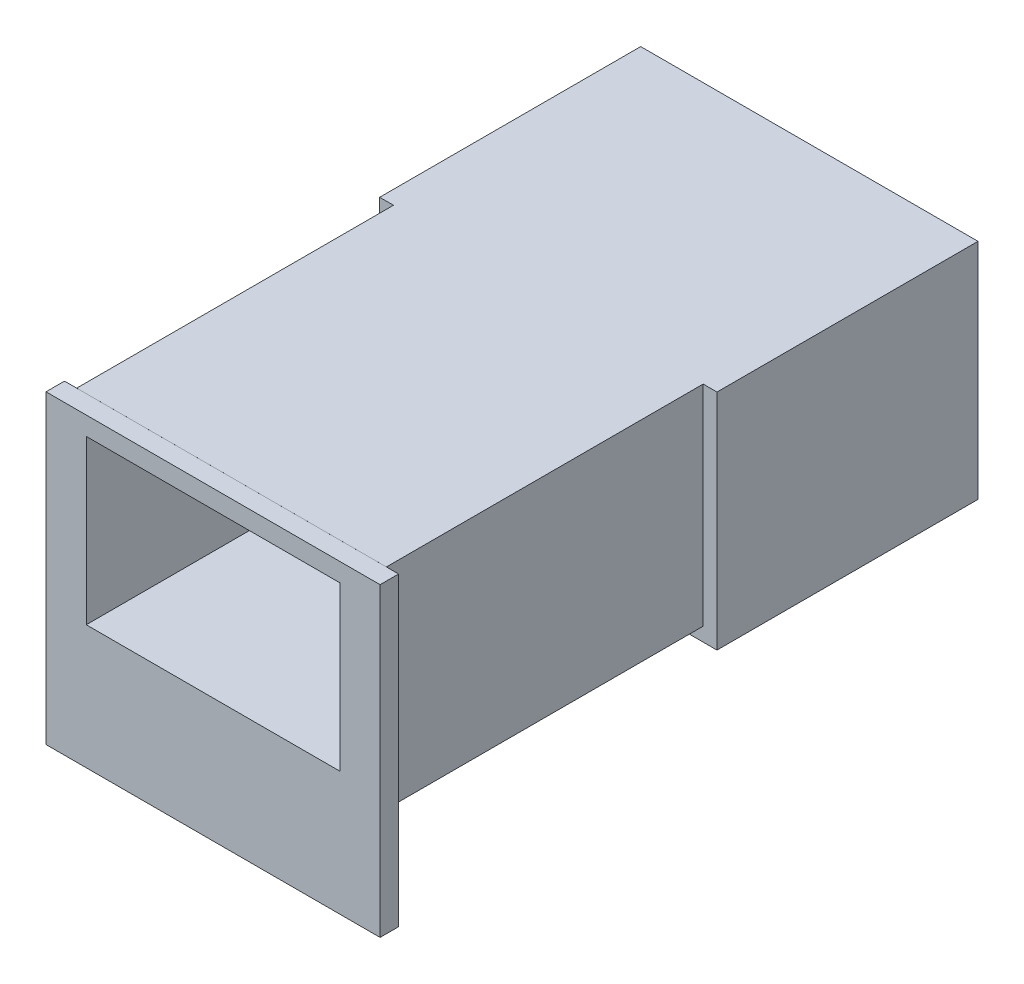
SolidWorks part; units mm, degrees
ref_plane "Alzado" through (0, 0, 0) normal (0, 0, 1) x (1, 0, 0)
ref_plane "Planta" through (0, 0, 0) normal (0, 1, 0) x (1, 0, 0)
ref_plane "Vista lateral" through (0, 0, 0) normal (1, 0, 0) x (0, 0, -1)
sketch "Croquis1" plane through (0, 0, 0) normal (0, 0, 1) x (1, 0, 0)
  line L1 (-37.1318, 17.9473) -> (16.1082, 17.9473)
  line L2 (-37.1318, 17.9473) -> (-37.1318, -17.3327)
  line L3 (-37.1318, -17.3327) -> (16.1082, -17.3327)
  line L4 (16.1082, 17.9473) -> (16.1082, -17.3327)
  line L5 (-33.9518, 15.0273) -> (12.9282, 15.0273)
  line L6 (-33.9518, 15.0273) -> (-33.9518, -14.1527)
  line L7 (-33.9518, -14.1527) -> (12.9282, -14.1527)
  line L8 (12.9282, 15.0273) -> (12.9282, -14.1527)
  dimension "D1" = 53.24
  dimension "D2" = 35.28
  dimension "D3" = 3.18
  dimension "D4" = 3.18
  dimension "D5" = 3.18
  dimension "D6" = 2.92
extrude "Saliente-Extruir2" add sketch "Croquis1" along normal blind 41.2
sketch "Croquis3" plane through (0, 0, 41.2) normal (0, 0, 1) x (1, 0, 0)
  line L1 (-34.9518, -15.1527) -> (13.9282, -15.1527)
  line L2 (-34.9518, -15.1527) -> (-34.9518, 17.9473)
  line L3 (-34.9518, 17.9473) -> (13.9282, 17.9473)
  line L4 (13.9282, -15.1527) -> (13.9282, 17.9473)
  line L5 (12.9282, -14.1527) -> (12.9282, 15.0273) construction
  line L7 (9.4982, 15.0273) -> (-30.5218, 15.0273)
  line L8 (9.4982, 15.0273) -> (9.4982, -10.7227)
  line L9 (9.4982, -10.7227) -> (-30.5218, -10.7227)
  line L10 (-30.5218, 15.0273) -> (-30.5218, -10.7227)
  line L12 (-34.9518, 17.9473) -> (13.9282, 17.9473)
  line L13 (-34.9518, 17.9473) -> (-34.9518, -15.1527)
  line L14 (-34.9518, -15.1527) -> (13.9282, -15.1527)
  line L15 (13.9282, 17.9473) -> (13.9282, -15.1527)
  line L16 (-30.5218, 15.0273) -> (9.4982, 15.0273)
  line L17 (-30.5218, 15.0273) -> (-30.5218, -10.7227)
  line L18 (-30.5218, -10.7227) -> (9.4982, -10.7227)
  line L19 (9.4982, 15.0273) -> (9.4982, -10.7227)
  line L20 (13.9282, -15.1527) -> (-34.9518, -15.1527)
  line L21 (13.9282, -15.1527) -> (13.9282, 17.9473)
  line L22 (13.9282, 17.9473) -> (-34.9518, 17.9473)
  line L23 (-34.9518, -15.1527) -> (-34.9518, 17.9473)
  line L24 (9.4982, -10.7227) -> (-30.5218, -10.7227)
  line L25 (9.4982, -10.7227) -> (9.4982, 15.0273)
  line L26 (9.4982, 15.0273) -> (-30.5218, 15.0273)
  line L27 (-30.5218, -10.7227) -> (-30.5218, 15.0273)
  dimension "D1" = 1
  dimension "D2" = 25.75
  dimension "D3" = 4.43
  dimension "D4" = 40.02
  dimension "D5" = 4.43
extrude "Saliente-Extruir11" add sketch "Croquis3" along normal blind 50 contours L10 L9 L8 L7 | L2 L3 L4 L1
sketch "Croquis15" plane through (0, 0, 91.2) normal (0, 0, 1) x (1, 0, 0)
  line L1 (15.8532, -30.2747) -> (-36.8768, -30.2747)
  line L2 (15.8532, -30.2747) -> (15.8532, 17.9453)
  line L3 (15.8532, 17.9453) -> (-36.8768, 17.9453)
  line L4 (-36.8768, -30.2747) -> (-36.8768, 17.9453)
  line L5 (13.9282, -15.1527) -> (13.9282, 17.9473) construction
  line L6 (-34.9518, -15.1527) -> (-34.9518, 17.9473) construction
  line L7 (-34.9518, -15.1527) -> (13.9282, -15.1527) construction
  line L10 (-30.5218, 15.0273) -> (9.4982, 15.0273)
  line L11 (-30.5218, 15.0273) -> (-30.5218, -10.7227)
  line L12 (-30.5218, -10.7227) -> (9.4982, -10.7227)
  line L13 (9.4982, 15.0273) -> (9.4982, -10.7227)
  dimension "D1" = 48.22
  dimension "D2" = 1.925
  dimension "D3" = 52.73
  dimension "D4" = 1.925
  dimension "D5" = 15.122
extrude "Saliente-Extruir13" add sketch "Croquis15" along normal blind 2.92
